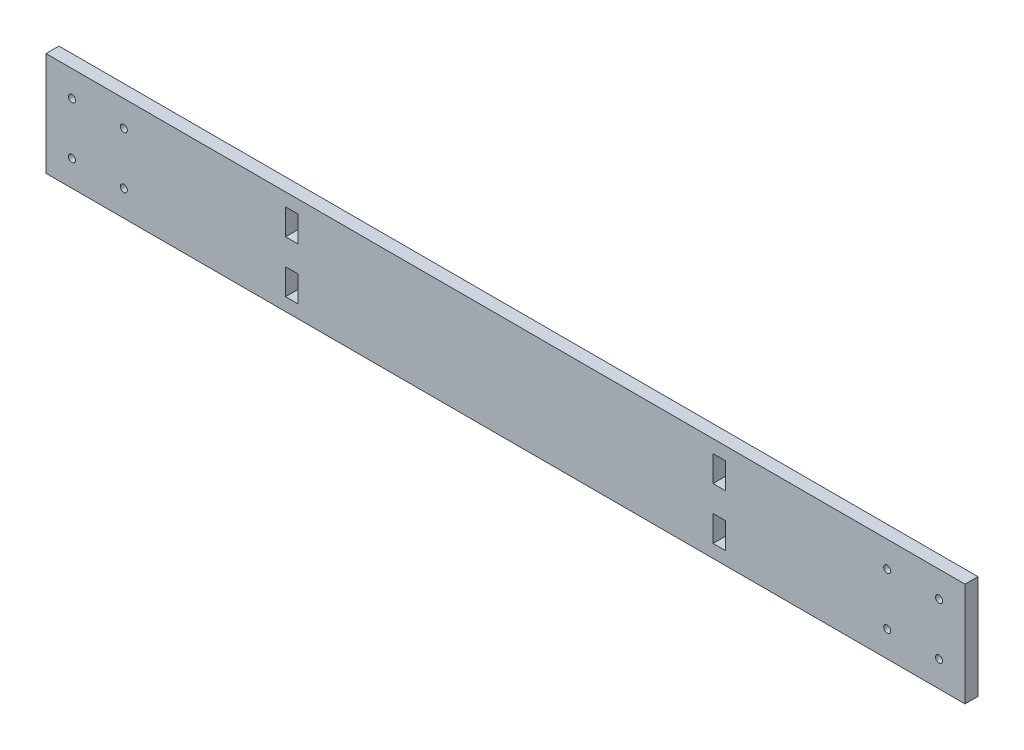
SolidWorks part; units mm, degrees
ref_plane "Front Plane" through (0, 0, 0) normal (0, 0, 1) x (1, 0, 0)
ref_plane "Top Plane" through (0, 0, 0) normal (0, 1, 0) x (1, 0, 0)
ref_plane "Right Plane" through (0, 0, 0) normal (1, 0, 0) x (0, 0, -1)
sketch "Sketch2" plane through (0, 0, 0) normal (0, 0, 1) x (1, 0, 0)
  line L1 (225.0249, -25.4) -> (-225.025, -25.4)
  line L2 (225.0249, -25.4) -> (225.0249, 25.4)
  line L3 (225.0249, 25.4) -> (-225.025, 25.4)
  line L4 (-225.025, -25.4) -> (-225.025, 25.4)
  line L5 (225.0249, -25.4) -> (-225.025, 25.4) construction
  line L6 (225.0249, 25.4) -> (-225.025, -25.4) construction
  point P0 (0, 0)
  dimension "D1" = 50.8
  dimension "D2" = 450.0499
extrude "Boss-Extrude1" add sketch "Sketch2" along normal mid plane 6.35
hole_wizard "#8-32 Tapped Hole1" positions "Sketch4" profile "Sketch3" tap size "#8-32" standard "ANSI Inch" end condition through all
sketch "Sketch4" plane through (0, 0, 3.175) normal (0, 0, 1) x (1, 0, 0)
  line L0 (0, 0) -> (0, 50000) construction
  line L1 (0, 0) -> (-50000, 0) construction
  line L2 (-199.6249, 0) -> (-199.6249, 50000) construction
  line L3 (199.6249, -4.135) -> (199.6249, 49995.865) construction
  point P7 (-212.3249, 12.7)
  point P9 (-212.3249, -12.7)
  point P11 (212.3249, 12.7)
  point P13 (212.3249, -12.7)
  point P15 (-186.9249, 12.7)
  point P17 (-186.9249, -12.7)
  point P19 (186.9249, 12.7)
  point P21 (186.9249, -12.7)
  dimension "D1" = 25.4
  dimension "D2" = 25.4
  dimension "D3" = 25.4
  dimension "D4" = 25.4
  dimension "D5" = 399.2499
sketch "Sketch3" plane through (-212.3249, 12.7, 3.175) normal (1, 0, 0) x (0, -1, 0)
  line L0 (0, 0) -> (0, 6.35)
  line L1 (0, 6.35) -> (1.7272, 6.35)
  line L2 (1.7272, 6.35) -> (1.7272, 0)
  line L5 (1.7272, 0) -> (0, 0)
  line L11 (0, -6.35) -> (0, 107.95) construction
  dimension "Thru Tap Drill Dia." = 3.4544
  dimension "Thru Tap Drill Depth" = 6.35
cosmetic thread "Hole Thread1" parameters "D2"=4.1656
cosmetic thread "Hole Thread2" parameters "D2"=4.1656
cosmetic thread "Hole Thread3" parameters "D2"=4.1656
cosmetic thread "Hole Thread4" parameters "D2"=4.1656
cosmetic thread "Hole Thread5" parameters "D2"=4.1656
cosmetic thread "Hole Thread6" parameters "D2"=4.1656
cosmetic thread "Hole Thread7" parameters "D2"=4.1656
cosmetic thread "Hole Thread8" parameters "D2"=4.1656
sketch "Sketch5" plane through (0, 0, 3.175) normal (0, 0, 1) x (1, 0, 0)
  line L0 (-107.696, 6.35) -> (-107.696, -6.35) construction
  line L1 (-107.696, 6.35) -> (-101.6, 6.35)
  line L2 (-107.696, 6.35) -> (-107.696, 19.05)
  line L3 (-107.696, 19.05) -> (-101.6, 19.05)
  line L4 (-101.6, 6.35) -> (-101.6, 19.05)
  line L5 (-101.6, -6.35) -> (-107.696, -6.35)
  line L6 (-101.6, -6.35) -> (-101.6, -19.05)
  line L7 (-101.6, -19.05) -> (-107.696, -19.05)
  line L8 (-107.696, -6.35) -> (-107.696, -19.05)
  line L9 (0, 0) -> (0, 50000) construction
  line L10 (107.696, 6.35) -> (107.696, 19.05)
  line L11 (107.696, 19.05) -> (101.6, 19.05)
  line L12 (101.6, 6.35) -> (101.6, 19.05)
  line L13 (107.696, 6.35) -> (101.6, 6.35)
  line L14 (101.6, -19.05) -> (107.696, -19.05)
  line L15 (101.6, -6.35) -> (101.6, -19.05)
  line L16 (101.6, -6.35) -> (107.696, -6.35)
  line L17 (107.696, -6.35) -> (107.696, -19.05)
  point P8 (-107.696, 0)
  dimension "D1" = 6.096
  dimension "D2" = 12.7
  dimension "D3" = 12.7
  dimension "D4" = 203.2
extrude "Cut-Extrude1" cut sketch "Sketch5" against normal through all
